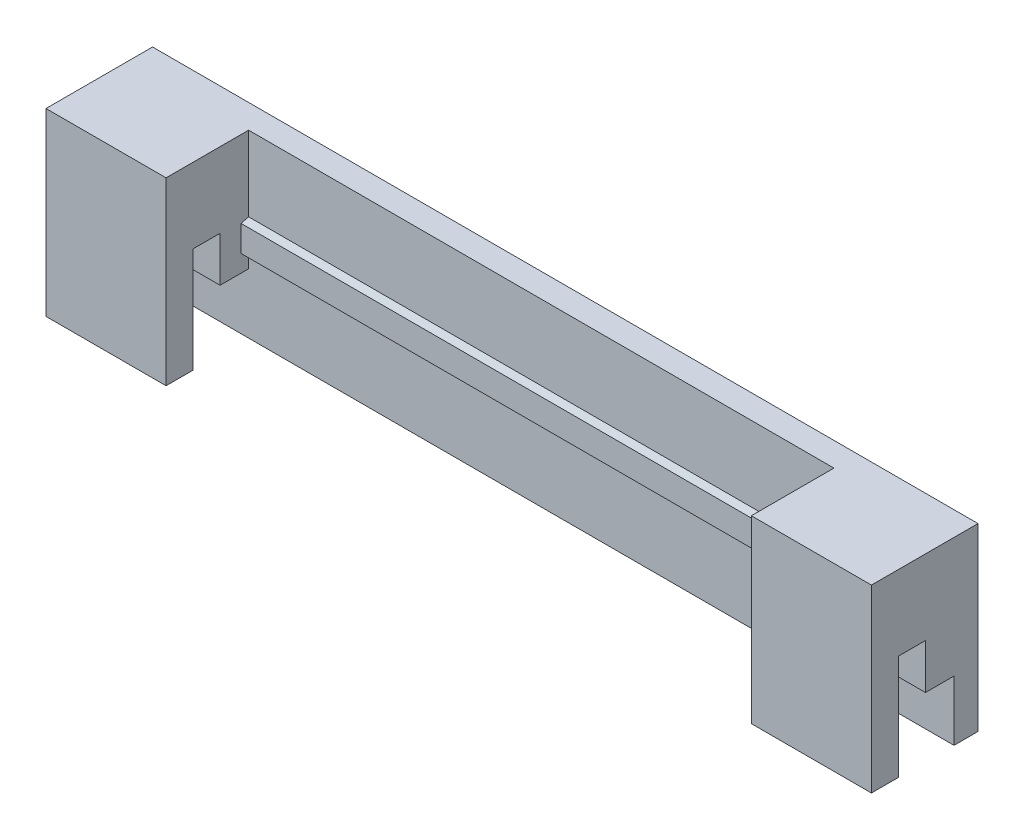
SolidWorks part; units mm, degrees
ref_plane "Front Plane" through (0, 0, 0) normal (0, 0, 1) x (1, 0, 0)
ref_plane "Top Plane" through (0, 0, 0) normal (0, 1, 0) x (1, 0, 0)
ref_plane "Right Plane" through (0, 0, 0) normal (1, 0, 0) x (0, 0, -1)
sketch "Sketch1" plane through (0, 0, 0) normal (0, 0, 1) x (1, 0, 0)
  line L1 (27.5, 6) -> (-27.5, 6)
  line L2 (27.5, 6) -> (27.5, -6)
  line L3 (27.5, -6) -> (-27.5, -6)
  line L4 (-27.5, 6) -> (-27.5, -6)
  line L5 (27.5, 6) -> (-27.5, -6) construction
  line L6 (27.5, -6) -> (-27.5, 6) construction
  point P0 (0, 0)
  dimension "D1" = 12
  dimension "D2" = 55
extrude "Boss-Extrude1" add sketch "Sketch1" along normal blind 1.6
sketch "Sketch2" plane through (0, 0, 1.6) normal (0, 0, 1) x (1, 0, 0)
  line L1 (-27.5, 6) -> (-19.5, 6)
  line L2 (-27.5, 6) -> (-27.5, -2)
  line L3 (-27.5, -2) -> (-19.5, -2)
  line L4 (-19.5, 6) -> (-19.5, -2)
  line L6 (27.5, 6) -> (19.5, 6)
  line L7 (27.5, 6) -> (27.5, -2)
  line L8 (27.5, -2) -> (19.5, -2)
  line L9 (19.5, 6) -> (19.5, -2)
  point P5 (-20.1122, 0.998)
  dimension "D1" = 8
  dimension "D2" = 8
extrude "Boss-Extrude2" add sketch "Sketch2" along normal blind 1.9
sketch "Sketch3" plane through (0, 0, 3.5) normal (0, 0, 1) x (1, 0, 0)
  line L0 (-19.5, -2) -> (-19.5, 6) construction
  line L1 (-27.5, 6) -> (-19.5, 6)
  line L2 (-27.5, 6) -> (-27.5, 1)
  line L3 (-27.5, 1) -> (-19.5, 1)
  line L4 (-19.5, 6) -> (-19.5, 1)
  line L5 (27.5, -2) -> (27.5, 6) construction
  line L6 (19.5, 6) -> (27.5, 6)
  line L7 (19.5, 6) -> (19.5, 1)
  line L8 (19.5, 1) -> (27.5, 1)
  line L9 (27.5, 6) -> (27.5, 1)
  dimension "D1" = 5
extrude "Boss-Extrude3" add sketch "Sketch3" along normal blind 1.8
sketch "Sketch4" plane through (0, 0, 5.3) normal (0, 0, 1) x (1, 0, 0)
  line L0 (-19.5, 1) -> (-19.5, 6) construction
  line L1 (-27.5, 6) -> (-19.5, 6)
  line L2 (-27.5, 6) -> (-27.5, -6)
  line L3 (-27.5, -6) -> (-19.5, -6)
  line L4 (-19.5, 6) -> (-19.5, -6)
  line L5 (19.5, 6) -> (19.5, 1) construction
  line L6 (27.5, 6) -> (19.5, 6)
  line L7 (27.5, 6) -> (27.5, -6)
  line L8 (27.5, -6) -> (19.5, -6)
  line L9 (19.5, 6) -> (19.5, -6)
  line L10 (-27.5, -6) -> (27.5, -6) construction
  point P14 (-27.5, -4.221)
extrude "Boss-Extrude6" add sketch "Sketch4" along normal blind 1.8
sketch "Sketch6" plane through (0, 0, 1.6) normal (0, 0, 1) x (1, 0, 0)
  line L0 (-27.5, -2) -> (-27.5, -6) construction
  line L1 (-27.5, 1) -> (27.5, 1)
  line L2 (-27.5, 1) -> (-27.5, -1)
  line L3 (-27.5, -1) -> (27.5, -1)
  line L4 (27.5, 1) -> (27.5, -1)
  line L5 (27.5, -6) -> (27.5, -2) construction
  line L6 (19.5, 6) -> (-19.5, 6) construction
  dimension "D1" = 5
  dimension "D2" = 2
extrude "Boss-Extrude7" add sketch "Sketch6" along normal blind 0.5 draft 15
